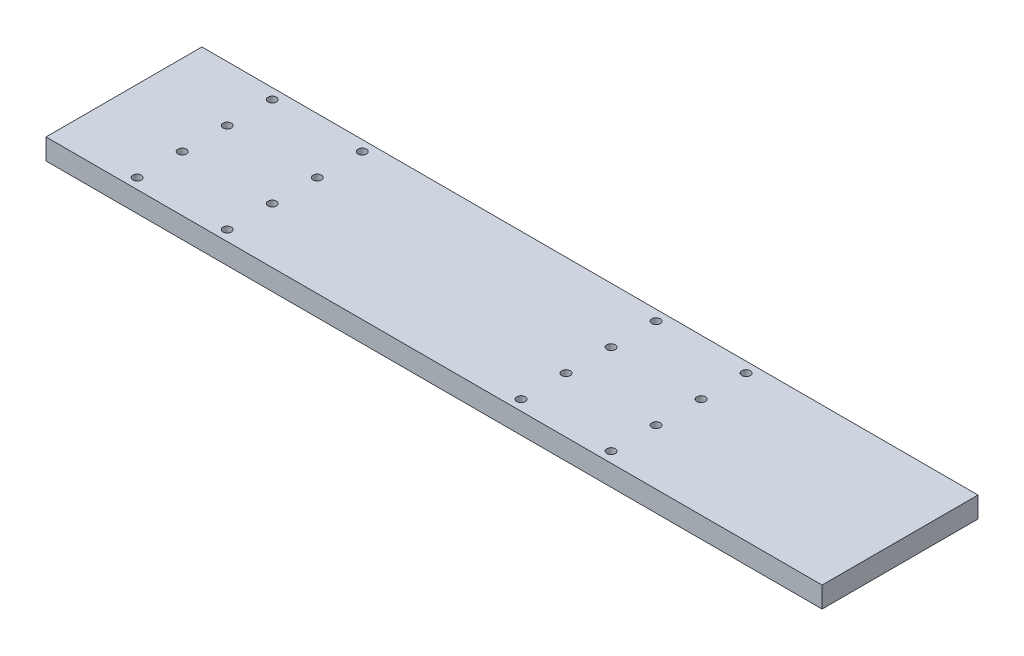
SolidWorks part; units mm, degrees
material "ABS PC"
ref_plane "Front Plane" through (0, 0, 0) normal (0, 0, 1) x (1, 0, 0)
ref_plane "Top Plane" through (0, 0, 0) normal (0, 1, 0) x (1, 0, 0)
ref_plane "Right Plane" through (0, 0, 0) normal (1, 0, 0) x (0, 0, -1)
sketch "Base-Shock-Plate" plane through (0, 0, 0) normal (0, 1, 0) x (1, 0, 0)
  line L0 (39.4, 51.7) -> (39.4, -3.7) construction
  line L1 (250.8, -3.7) -> (0, -3.7)
  line L2 (250.8, -3.7) -> (250.8, 51.7)
  line L3 (250.8, 51.7) -> (0, 51.7)
  line L4 (0, -3.7) -> (0, 51.7) construction
  line L6 (136.4, 51.7) -> (136.4, -3.7) construction
  line L7 (175.8, 51.7) -> (175.8, -3.7) construction
  line L8 (0, 51.7) -> (-25, 51.7)
  line L9 (-25, 51.7) -> (-25, -3.7)
  line L10 (-25, -3.7) -> (0, -3.7)
  circle A8 centre (140.1, 16) radius 1.5
  circle A9 centre (140.1, 48) radius 1.5
  circle A10 centre (172.1, 0) radius 1.5
  circle A11 centre (172.1, 32) radius 1.5
  circle A12 centre (140.1, 32) radius 1.5
  circle A13 centre (172.1, 48) radius 1.5
  circle A14 centre (172.1, 16) radius 1.5
  circle A15 centre (140.1, 0) radius 1.5
  circle A16 centre (3.7, 16) radius 1.5
  circle A17 centre (3.7, 48) radius 1.5
  circle A18 centre (35.7, 0) radius 1.5
  circle A19 centre (35.7, 32) radius 1.5
  circle A20 centre (3.7, 32) radius 1.5
  circle A21 centre (35.7, 48) radius 1.5
  circle A22 centre (35.7, 16) radius 1.5
  circle A23 centre (3.7, 0) radius 1.5
  dimension "D5" = 3.7
  dimension "D7" = 3.7
  dimension "D10" = 16
  dimension "D17" = 3
  dimension "D18" = 3
  dimension "D19" = 3
  dimension "D20" = 3
  dimension "D13" = 3
  dimension "D14" = 3
  dimension "D16" = 3
  dimension "D21" = 3
  dimension "D34" = 16
  dimension "D52" = 3
  dimension "D53" = 3
  dimension "D54" = 3
  dimension "D55" = 3
  dimension "D56" = 3
  dimension "D57" = 3
  dimension "D58" = 3
  dimension "D59" = 3
  dimension "D1" = 250.8
  dimension "D2" = 55.4
  dimension "D6" = 3.7
  dimension "D8" = 3.7
  dimension "D9" = 16
  dimension "D11" = 39.4
  dimension "D12" = 97
  dimension "D15" = 39.4
  dimension "D22" = 3.7
  dimension "D23" = 3.7
  dimension "D24" = 3.7
  dimension "D25" = 16
  dimension "D26" = 3.7
  dimension "D27" = 3.7
  dimension "D28" = 3.7
  dimension "D29" = 3.7
  dimension "D30" = 3.7
  dimension "D31" = 16
  dimension "D32" = 16
  dimension "D33" = 16
  dimension "D35" = 16
  dimension "D36" = 16
  dimension "D37" = 32
  dimension "D38" = 32
  dimension "D39" = 32
  dimension "D40" = 32
  dimension "D41" = 16
  dimension "D42" = 16
  dimension "D43" = 16
  dimension "D44" = 3.7
  dimension "D45" = 3.7
  dimension "D46" = 3.7
  dimension "D47" = 3.7
  dimension "D48" = 32
  dimension "D49" = 32
  dimension "D50" = 32
  dimension "D51" = 32
  dimension "D60" = 25
  dimension "D61" = 275.8
extrude "Base-Shock-Plate-Extrude" add sketch "Base-Shock-Plate" along normal blind 7.4
